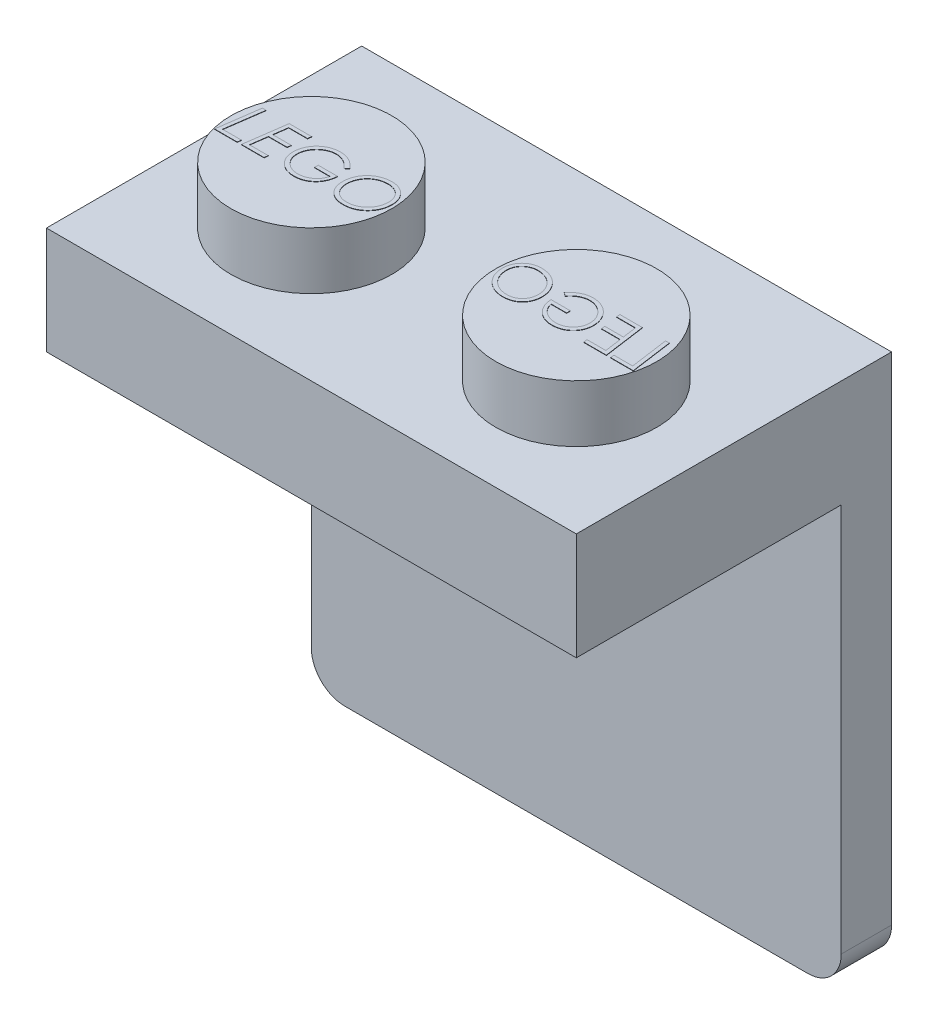
SolidWorks part; units mm, degrees
ref_plane "Front Plane" through (0, 0, 0) normal (0, 0, 1) x (1, 0, 0)
ref_plane "Top Plane" through (0, 0, 0) normal (0, 1, 0) x (1, 0, 0)
ref_plane "Right Plane" through (0, 0, 0) normal (1, 0, 0) x (0, 0, -1)
sketch "Sketch1" plane through (0, 0, 0) normal (0, 1, 0) x (1, 0, 0)
  line L0 (0, 0) -> (7.9, 0)
  line L1 (7.9, 0) -> (7.9, 7.9)
  line L2 (0, 0) -> (0, 7.9)
  line L3 (0, 7.9) -> (7.9, 7.9)
  dimension "D1" = 7.9
  dimension "D2" = 7.9
  dimension "D3" = 7.9
extrude "Boss-Extrude1" add sketch "Sketch1" along normal blind 3.2
sketch "Sketch2" plane through (0, 3.2, 0) normal (0, 1, 0) x (1, 0, 0)
  line L0 (0, 7.9) -> (7.9, 0) construction
  circle A0 centre (3.95, 3.95) radius 2.4
extrude "Boss-Extrude2" add sketch "Sketch2" along normal blind 1.7
sketch "Sketch3" plane through (0, 4.9, 0) normal (0, 1, 0) x (1, 0, 0)
  line L0 (1.625, 3.3549) -> (6.275, 3.3549) construction
  circle A0 centre (3.95, 3.95) radius 2.4 construction
  circle A1 centre (3.95, 3.95) radius 2.4 construction
  text T0 "<i>LEGO</i>" font "Century Gothic" height 1.25
extrude "Boss-Extrude4" add sketch "Sketch3" along normal blind 0.01
sketch "Sketch4" plane through (0, 0, 0) normal (0, -1, 0) x (1, 0, 0)
  line L0 (7.9, -7.9) -> (0, -7.9) construction
  line L1 (7.3, -7.3) -> (0.6204, -7.3)
  line L2 (7.3, -7.3) -> (7.3, -0.6204)
  line L3 (7.3, -0.6204) -> (0.6204, -0.6204)
  line L4 (0.6204, -7.3) -> (0.6204, -0.6204)
  line L5 (7.9, 0) -> (7.9, -7.9) construction
  dimension "D1" = 0.6
  dimension "D2" = 0.6
extrude "Cut-Extrude1" cut sketch "Sketch4" against normal blind 2.01 contours L2 L1 L4 L3
sketch "Sketch5" plane through (0, 3.2, 0) normal (0, 1, 0) x (1, 0, 0)
  line L1 (1.4581, 1.5578) -> (6.3695, 1.5578)
  line L2 (1.4581, 1.5578) -> (1.4581, 6.3652)
  line L3 (1.4581, 6.3652) -> (6.3695, 6.3652)
  line L4 (6.3695, 1.5578) -> (6.3695, 6.3652)
  circle A1 centre (6.3695, 6.3652) radius 1.0161
  circle A2 centre (6.3695, 1.5578) radius 1.0061
  circle A3 centre (1.4581, 1.5578) radius 1.0219
  circle A4 centre (1.4581, 6.3652) radius 1.0411
  circle M5 centre (3.95, 3.95) radius 2.4
extrude "Boss-Extrude5" add sketch "Sketch5" against normal blind 2.01 contours L1 A2 L4 | L2 A3 L1 | L1 A3 L2 | L4 A2 L1 M5 | L4 A1 L3 | L3 A1 L4 | L2 A4 L3 | L3 A4 L2
mirror "Mirror1" about plane through (7.9, 3.2, 0) normal (-1, 0, 0) of bodies 106
sketch "Sketch6" plane through (0, 0, -7.9) normal (0, 0, -1) x (-1, 0, 0)
  line L1 (-15.8, 3.2) -> (0, 3.2)
  line L2 (-15.8, 3.2) -> (-15.8, -12.6)
  line L3 (-15.8, -12.6) -> (0, -12.6)
  line L4 (0, 3.2) -> (0, -12.6)
  dimension "D1" = 15.8
extrude "Boss-Extrude6" add sketch "Sketch6" along normal blind 1.5
sketch "Sketch7" plane through (0, 0, -7.9) normal (0, 0, 1) x (1, 0, 0)
  line L0 (7.9, 3.2) -> (7.9, -12.6)
  line L1 (0, 3.2) -> (15.8, 3.2) construction
  line L2 (15.8, -12.6) -> (0, -12.6) construction
  line L3 (15.8, -4.7) -> (0, -4.7)
  line L4 (15.8, 3.2) -> (15.8, -12.6) construction
  line L5 (0, -12.6) -> (0, 3.2) construction
  line L6 (15.8, 3.2) -> (0, -12.6)
  line L7 (15.8, -4.7) -> (7.9, 3.2)
  circle A0 centre (11.85, -0.75) radius 2.4
  circle A1 centre (11.85, -0.75) radius 1.7
  circle A2 centre (3.95, -0.75) radius 2.4
  circle A3 centre (3.95, -0.75) radius 1.7
  circle A4 centre (3.95, -8.65) radius 2.4
  circle A5 centre (3.95, -8.65) radius 1.7
  circle A6 centre (11.85, -8.65) radius 2.4
  circle A7 centre (11.85, -8.65) radius 1.7
  line M2 (15.8, 0) -> (0, 0)
  dimension "D1" = 4.8
  dimension "D2" = 3.4
  dimension "D3" = 2
  dimension "D4" = 2
extrude "Boss-Extrude7" add sketch "Sketch7" against normal blind 2.9 contours A3 A2 M2 | A4 | A5 | A7 | A6 | A0 | A1
fillet "Fillet1" radius 1 2 edges at (0, -12.6, -8.65) (15.8, -12.6, -8.65)
